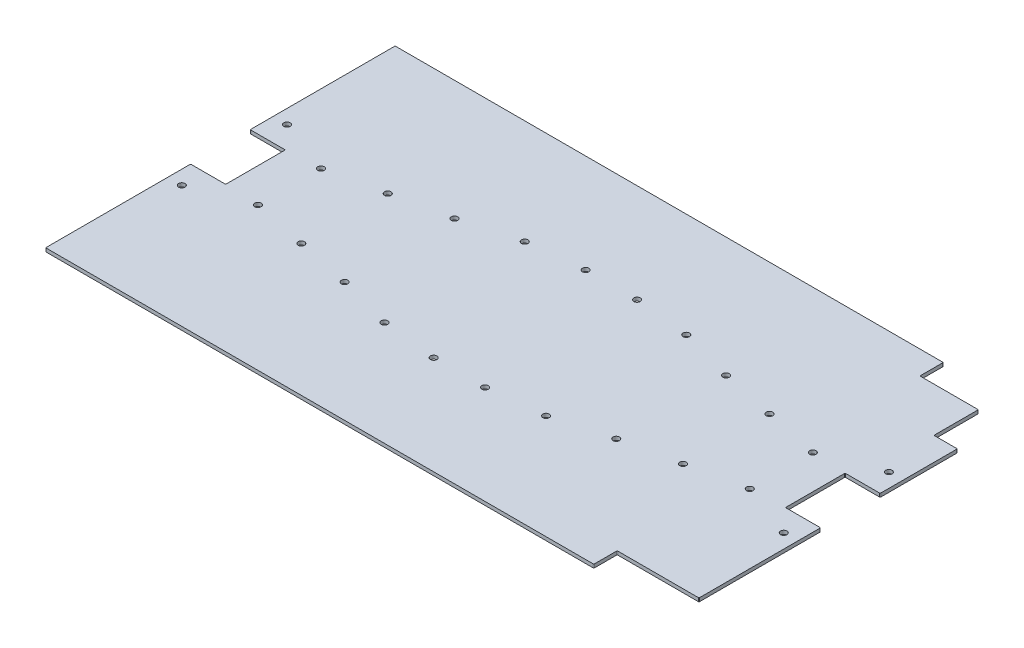
SolidWorks part; units mm, degrees
ref_plane "Front Plane" through (0, 0, 0) normal (0, 0, 1) x (1, 0, 0)
ref_plane "Top Plane" through (0, 0, 0) normal (0, 1, 0) x (1, 0, 0)
ref_plane "Right Plane" through (0, 0, 0) normal (1, 0, 0) x (0, 0, -1)
sketch "Sketch1" plane through (0, 0, 0) normal (0, 1, 0) x (1, 0, 0)
  line L1 (269.5, -149.5) -> (-269.5, -149.5)
  line L2 (269.5, -149.5) -> (269.5, 149.5)
  line L3 (269.5, 149.5) -> (-269.5, 149.5)
  line L4 (-269.5, -149.5) -> (-269.5, 149.5)
  line L5 (269.5, -149.5) -> (-269.5, 149.5) construction
  line L6 (269.5, 149.5) -> (-269.5, -149.5) construction
  point P0 (0, 0)
  dimension "D1" = 539
  dimension "D2" = 299
extrude "Boss-Extrude1" add sketch "Sketch1" along normal blind 3
sketch "Sketch5" plane through (0, 3, 0) normal (0, 1, 0) x (1, 0, 0)
  line L0 (269.5, 149.5) -> (199.5, 149.5)
  line L1 (269.5, 149.5) -> (-269.5, 149.5) construction
  line L2 (199.5, 149.5) -> (199.5, 129.5)
  line L3 (199.5, 129.5) -> (249.5, 129.5)
  line L4 (249.5, 129.5) -> (249.5, 91.5)
  line L5 (249.5, 91.5) -> (269.5, 91.5)
  line L6 (269.5, -149.5) -> (269.5, 149.5) construction
  line L7 (269.5, 91.5) -> (269.5, 149.5)
  line L8 (269.5, -149.5) -> (199.5, -149.5)
  line L9 (-269.5, -149.5) -> (269.5, -149.5) construction
  line L10 (199.5, -149.5) -> (199.5, -129.5)
  line L11 (199.5, -129.5) -> (269.5, -129.5)
  line L12 (269.5, -129.5) -> (269.5, -149.5)
  dimension "D1" = 20
  dimension "D2" = 20
  dimension "D3" = 20
  dimension "D4" = 70
  dimension "D5" = 70
  dimension "D6" = 58
extrude "Cut-Extrude2" cut sketch "Sketch5" against normal through all
sketch "Sketch2" plane through (0, 3, 0) normal (0, 1, 0) x (1, 0, 0)
  line L0 (0, 0) -> (-269.5, 0) construction
  line L1 (-269.5, 149.5) -> (-269.5, -149.5) construction
  line L3 (-239.5, -25.5) -> (-269.5, -25.5)
  line L4 (-239.5, -25.5) -> (-239.5, 25.5)
  line L5 (-239.5, 25.5) -> (-269.5, 25.5)
  line L6 (-269.5, -25.5) -> (-269.5, 25.5)
  line L7 (-239.5, -25.5) -> (-269.5, 25.5) construction
  line L8 (-239.5, 25.5) -> (-269.5, -25.5) construction
  point P5 (-254.5, 0)
  dimension "D1" = 30
  dimension "D2" = 51
extrude "Cut-Extrude1" cut sketch "Sketch2" against normal through all
mirror "Mirror1" about plane through (0, 0, 0) normal (1, 0, 0) of "Cut-Extrude1"
sketch "Sketch3" plane through (0, 3, 0) normal (0, 1, 0) x (1, 0, 0)
  point P0 (-255, -105)
  dimension "D1" = 255
  dimension "D2" = 105
sketch "Sketch6" plane through (0, 3, 0) normal (0, 1, 0) x (1, 0, 0)
  circle A1 centre (-69.1, -60) radius 2.5
  circle A2 centre (-69.1, -60) radius 2.5
  circle A3 centre (-116.2, -47.0034) radius 2.5
  circle A4 centre (-116.2, -47.0034) radius 2.5
  circle A5 centre (-163.3, -36.992) radius 2.5
  circle A6 centre (-163.3, -36.992) radius 2.5
  circle A7 centre (-210.4, -26.9806) radius 2.5
  circle A8 centre (-210.4, -26.9806) radius 2.5
  circle A9 centre (-257.5, -45) radius 2.5
  circle A10 centre (-257.5, -45) radius 2.5
  circle A11 centre (-22, -65) radius 2.5
  circle A12 centre (-22, -65) radius 2.5
  dimension "D1" = 0
  dimension "D2" = 0
  dimension "D3" = 0
  dimension "D4" = 0
  dimension "D5" = 0
  dimension "D6" = 0
hole_wizard "Ø5.5 (5.5) Diameter Hole1" positions "3DSketch1" profile "Sketch4" hole size "Ø5.5" standard "ANSI Metric" end condition through all
sketch3d "3DSketch1"
  point P3 (-257.5, 3, 45)
  point P6 (-210.4, 3, 26.9806)
  point P9 (-163.3, 3, 36.992)
  point P12 (-116.2, 3, 47.0034)
  point P15 (-69.1, 3, 60)
  point P18 (-22, 3, 65)
sketch "Sketch4" plane through (-257.5, 3, 45) normal (1, 0, 0) x (0, 0, 1)
  line L0 (0, 0) -> (0, 3)
  line L1 (0, 3) -> (2.75, 3)
  line L2 (2.75, 3) -> (2.75, 0)
  line L5 (2.75, 0) -> (0, 0)
  line L11 (0, -6.35) -> (0, 107.95) construction
  dimension "Thru Hole Dia." = 5.5
  dimension "Thru Hole Depth" = 3
mirror "Mirror2" about plane through (0, 0, 0) normal (1, 0, 0) of "Ø5.5 (5.5) Diameter Hole1"
mirror "Mirror3" about plane through (0, 0, 0) normal (0, 0, 1) of "Mirror2", "Ø5.5 (5.5) Diameter Hole1"
fillet "Fillet1" radius 0.5 18 edges at (239.5, 1.5, 25.5) (239.5, 1.5, -25.5) (269.5, 1.5, -25.5) (269.5, 1.5, -91.5) (249.5, 1.5, -91.5) (249.5, 1.5, -129.5) (199.5, 1.5, -129.5) (199.5, 1.5, -149.5) (-269.5, 1.5, -149.5) (-239.5, 1.5, -25.5) (-239.5, 1.5, 25.5) (-269.5, 1.5, 25.5) (-269.5, 1.5, 149.5) (199.5, 1.5, 149.5) (199.5, 1.5, 129.5) (269.5, 1.5, 129.5) (269.5, 1.5, 25.5) (-269.5, 1.5, -25.5)
